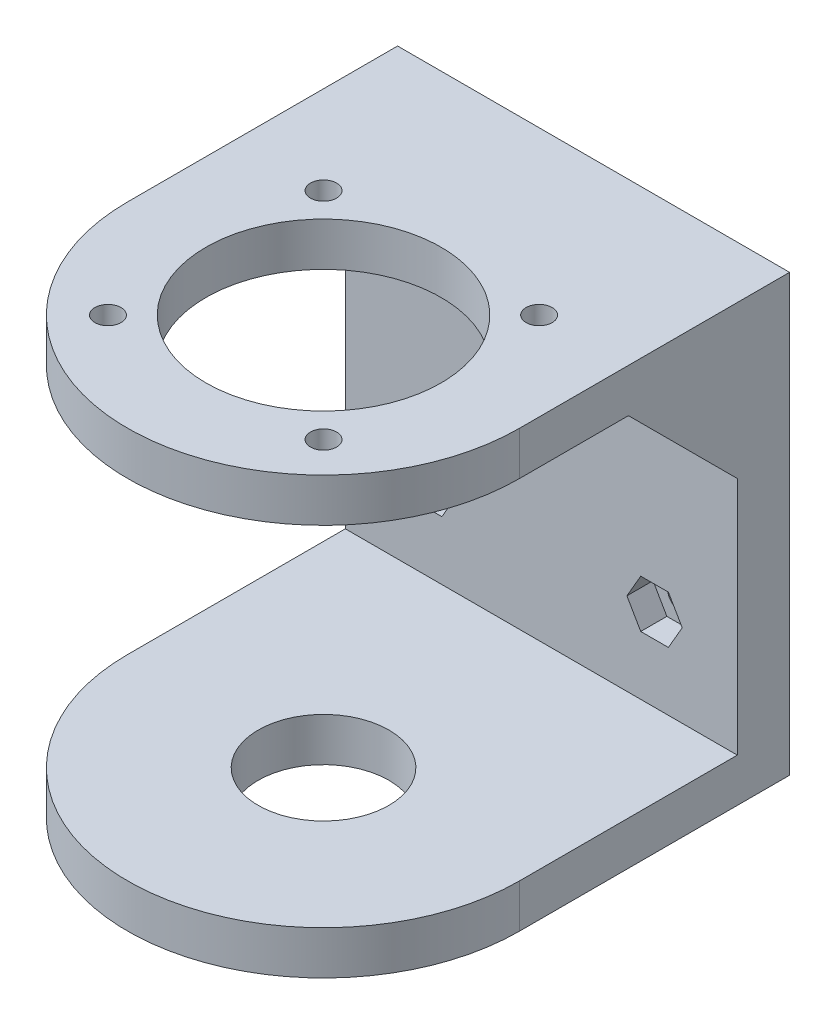
SolidWorks part; units mm, degrees
ref_plane "前视基准面" through (0, 0, 0) normal (0, 0, 1) x (1, 0, 0)
ref_plane "上视基准面" through (0, 0, 0) normal (0, 1, 0) x (1, 0, 0)
ref_plane "右视基准面" through (0, 0, 0) normal (1, 0, 0) x (0, 0, -1)
sketch "草图1" plane through (0, 0, 0) normal (0, 1, 0) x (1, 0, 0)
  line L1 (0, 0) -> (45, 0)
  line L2 (0, 0) -> (0, 47.5)
  line L3 (0, 47.5) -> (45, 47.5)
  line L4 (45, 0) -> (45, 47.5)
  circle A0 centre (22.5, 22.5) radius 13.5
  circle A1 centre (34.875, 34.875) radius 1.5
  circle A2 centre (34.875, 10.125) radius 1.5
  circle A3 centre (10.125, 10.125) radius 1.5
  circle A4 centre (10.125, 34.875) radius 1.5
  arc A6 (0, 22.5) -> (45, 22.5) centre (22.5, 22.5) ccw
  point P18 (22.5, 22.5)
  dimension "D1" = 27
  dimension "D2" = 3
  dimension "D4" = 24.75
  dimension "D5" = 22.5
  dimension "D6" = 22.5
  dimension "D7" = 22.5
  dimension "D8" = 25
  dimension "D9" = 12.375
  dimension "D3" = 4
extrude "凸台-拉伸1" add sketch "草图1" along normal blind 5 contours A6 L4 L3 L2 A4 A3 A2 A1 A0
ref_plane "基准面1" through (0, 5, 0) normal (0, 1, 0) x (1, 0, 0)
sketch "草图2" plane through (0, 5, 0) normal (0, 1, 0) x (1, 0, 0)
  line L1 (0, 47.5) -> (45, 47.5)
  line L2 (0, 47.5) -> (0, 53.5)
  line L3 (0, 53.5) -> (45, 53.5)
  line L4 (45, 47.5) -> (45, 53.5)
  dimension "D1" = 6
extrude "凸台-拉伸2" add sketch "草图2" against normal blind 45
ref_plane "基准面2" through (0, 0, -53.5) normal (0, 0, -1) x (-1, 0, 0)
sketch "草图4" plane through (0, 0, -53.5) normal (0, 0, -1) x (-1, 0, 0)
  line L0 (-45, -17.5) -> (0, -17.5) construction
  line L1 (-45, -40) -> (-45, 5) construction
  line L2 (0, -40) -> (0, 5) construction
  line L3 (-22.5, -17.5) -> (-22.5, 5) construction
  line L4 (24.75, 5) -> (-24.75, 5) construction
  circle A0 centre (-9.5, -4.5) radius 1.5
  circle A1 centre (-9.5, -30.5) radius 1.5
  circle A2 centre (-35.5, -30.5) radius 1.5
  circle A3 centre (-35.5, -4.5) radius 1.5
  point P21 (-22.5, -17.5)
  dimension "D1" = 3
  dimension "D3" = 26
  dimension "D4" = 13
  dimension "D5" = 13
  dimension "D6" = 13
  dimension "D2" = 4
extrude "切除-拉伸1" cut sketch "草图4" against normal up to next
ref_plane "基准面3" through (0, 0, 0) normal (-1, 0, 0) x (0, 0, 1)
sketch "草图5" plane through (0, 0, 0) normal (-1, 0, 0) x (0, 0, 1)
  line L0 (-47.5, 0) -> (-35, 0)
  line L1 (-22.5, 0) -> (-47.5, 0) construction
  line L2 (-35, 0) -> (-47.5, -12.5)
  line L3 (-47.5, -40) -> (-47.5, 0) construction
  line L4 (-47.5, -12.5) -> (-47.5, 0)
  dimension "D1" = 12.5
extrude "凸台-拉伸3" add sketch "草图5" against normal blind 3
ref_plane "基准面4" through (45, 0, 0) normal (1, 0, 0) x (0, 0, -1)
sketch "草图6" plane through (45, 0, 0) normal (1, 0, 0) x (0, 0, -1)
  line L0 (35, 0) -> (47.5, 0)
  line L1 (47.5, 0) -> (47.5, -12.5)
  line L2 (47.5, -12.5) -> (35, 0)
extrude "凸台-拉伸4" add sketch "草图6" against normal blind 3
fillet "圆角1" radius 1 1 edges at (22.5, 0, -47.5)
ref_plane "基准面5" through (0, 0, -47.5) normal (0, 0, 1) x (1, 0, 0)
sketch "草图7" plane through (0, 0, -47.5) normal (0, 0, 1) x (1, 0, 0)
  line L0 (22.5, -1) -> (22.5, -40) construction
  line L7 (3, -1) -> (42, -1) construction
  line L8 (0, -40) -> (45, -40) construction
  line L9 (22.5, -20.5) -> (45, -20.5) construction
  line L10 (45, -17.05) -> (45, 17.05) construction
  line L11 (11.0877, -33.25) -> (7.9123, -33.25)
  line L12 (37.0877, -33.25) -> (38.6754, -30.5)
  line L13 (38.6754, -30.5) -> (37.0877, -27.75)
  line L14 (37.0877, -27.75) -> (33.9123, -27.75)
  line L15 (33.9123, -27.75) -> (32.3246, -30.5)
  line L16 (32.3246, -30.5) -> (33.9123, -33.25)
  line L17 (33.9123, -33.25) -> (37.0877, -33.25)
  line L18 (12.6754, -30.5) -> (11.0877, -33.25)
  line L19 (11.0877, -27.75) -> (12.6754, -30.5)
  line L20 (7.9123, -27.75) -> (11.0877, -27.75)
  line L21 (6.3246, -30.5) -> (7.9123, -27.75)
  line L22 (7.9123, -33.25) -> (6.3246, -30.5)
  line L29 (35.5, -4.5) -> (35.5, -30.5) construction
  line L30 (35.5, -17.5) -> (45, -17.5) construction
  line L31 (33.9123, -1.75) -> (37.0877, -1.75)
  line L32 (32.3246, -4.5) -> (33.9123, -1.75)
  line L33 (33.9123, -7.25) -> (32.3246, -4.5)
  line L34 (37.0877, -7.25) -> (33.9123, -7.25)
  line L35 (38.6754, -4.5) -> (37.0877, -7.25)
  line L36 (37.0877, -1.75) -> (38.6754, -4.5)
  line L37 (7.9123, -1.75) -> (6.3246, -4.5)
  line L38 (6.3246, -4.5) -> (7.9123, -7.25)
  line L39 (7.9123, -7.25) -> (11.0877, -7.25)
  line L40 (11.0877, -7.25) -> (12.6754, -4.5)
  line L41 (12.6754, -4.5) -> (11.0877, -1.75)
  line L42 (11.0877, -1.75) -> (7.9123, -1.75)
  circle A0 centre (35.5, -30.5) radius 2.75 construction
  dimension "D1" = 5.5
extrude "切除-拉伸2" cut sketch "草图7" against normal blind 3
ref_plane "基准面6" through (0, -40, 0) normal (0, -1, 0) x (-1, 0, 0)
sketch "草图8" plane through (0, -40, 0) normal (0, -1, 0) x (-1, 0, 0)
  line L3 (-45, 53.5) -> (-45, 22.5)
  line L4 (0, 53.5) -> (-45, 53.5)
  line L5 (0, 22.5) -> (0, 53.5)
  line L6 (-45, 53.5) -> (-45, 22.5)
  line L7 (0, 53.5) -> (-45, 53.5)
  line L8 (0, 22.5) -> (0, 53.5)
  arc A1 (-45, 22.5) -> (0, 22.5) centre (-22.5, 22.5) ccw
  arc A2 (-45, 22.5) -> (0, 22.5) centre (-22.5, 22.5) ccw
  dimension "D1" = 0
extrude "凸台-拉伸5" add sketch "草图8" along normal blind 5
sketch "草图9" plane through (0, -40, 0) normal (0, -1, 0) x (-1, 0, 0)
  circle A0 centre (-22.5, 22.5) radius 7.5
  dimension "D1" = 15
extrude "切除-拉伸3" cut sketch "草图9" along normal up to next
